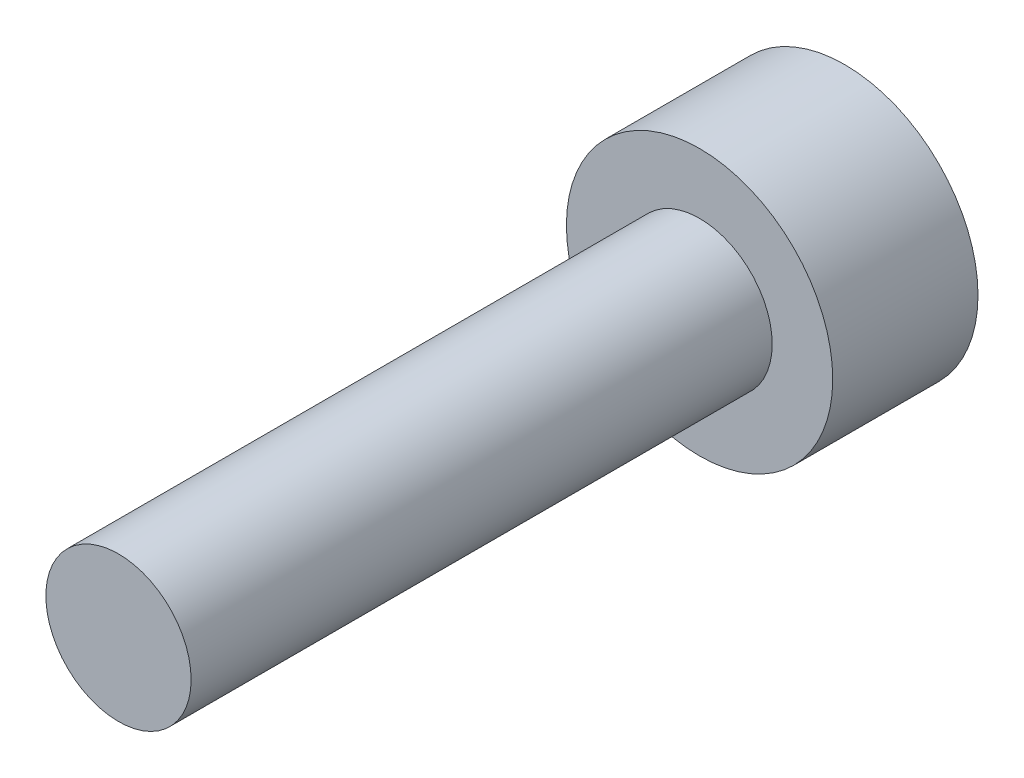
SolidWorks part; units mm, degrees
material "AISI 304"
ref_plane "Alzado" through (0, 0, 0) normal (0, 0, 1) x (1, 0, 0)
ref_plane "Planta" through (0, 0, 0) normal (0, 1, 0) x (1, 0, 0)
ref_plane "Vista lateral" through (0, 0, 0) normal (1, 0, 0) x (0, 0, -1)
sketch "Sk_Cabeza" plane through (0, 0, 0) normal (0, 0, 1) x (1, 0, 0)
  circle A0 centre (0, 0) radius 2.75
  dimension "D1" = 5.5
extrude "Cabeza" add sketch "Sk_Cabeza" along normal blind 3 from offset 3
sketch "Sk_Cuerpo" plane through (0, 0, 0) normal (0, 0, 1) x (1, 0, 0)
  circle A0 centre (0, 0) radius 1.5
  dimension "D1" = 3
extrude "Cuerpo" add sketch "Sk_Cuerpo" along normal blind 12
sketch "Sk_Hexagono_interior" plane through (0, 0, 0) normal (0, 0, 1) x (1, 0, 0)
  line L1 (0, -1.4434) -> (1.25, -0.7217)
  line L2 (1.25, -0.7217) -> (1.25, 0.7217)
  line L3 (1.25, 0.7217) -> (0, 1.4434)
  line L4 (0, 1.4434) -> (-1.25, 0.7217)
  line L5 (-1.25, 0.7217) -> (-1.25, -0.7217)
  line L6 (-1.25, -0.7217) -> (0, -1.4434)
  circle A0 centre (0, 0) radius 1.25 construction
  dimension "D1" = 2.5
extrude "Hexagono_interior" cut sketch "Sk_Hexagono_interior" along normal blind 1.5 from offset 3
